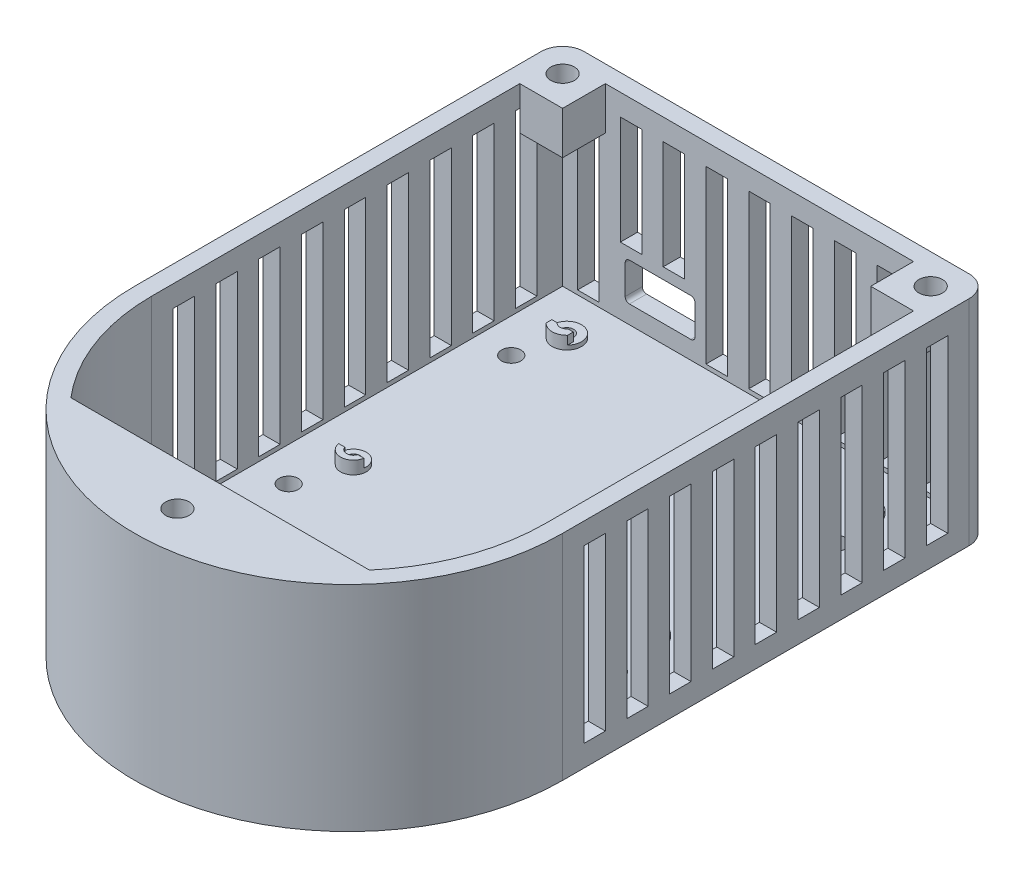
SolidWorks part; units mm, degrees
ref_plane "前视基准面" through (0, 0, 0) normal (0, 0, 1) x (1, 0, 0)
ref_plane "上视基准面" through (0, 0, 0) normal (0, 1, 0) x (1, 0, 0)
ref_plane "右视基准面" through (0, 0, 0) normal (1, 0, 0) x (0, 0, -1)
sketch "草图1" plane through (0, 0, 0) normal (0, 1, 0) x (1, 0, 0)
  line L2 (-50, -50) -> (-50, 50)
  line L3 (-50, 50) -> (50, 50)
  line L4 (50, -50) -> (50, 50)
  line L5 (-50, -50) -> (50, 50) construction
  line L6 (-50, 50) -> (50, -50) construction
  arc A1 (-50, -50) -> (50, -50) centre (0, -50) ccw
  point P0 (0, 0)
  dimension "D3" = 50
  dimension "D1" = 100
  dimension "D2" = 100
extrude "凸台-拉伸1" add sketch "草图1" along normal blind 50
shell "抽壳1" thickness 4
sketch "草图2" plane through (0, 4, 0) normal (0, 1, 0) x (1, 0, 0)
  line L0 (0, 0) -> (0, 50000) construction
  circle A7 centre (35.6323, -14.6895) radius 3
  circle A9 centre (35.7606, 35.3104) radius 3
  circle A10 centre (-35, 36) radius 3.4255
  circle A11 centre (-34.3676, -14.5099) radius 3
  dimension "D3" = 6
  dimension "D4" = 6
  dimension "D1" = 6
  dimension "D2" = 6.851
extrude "凸台-拉伸2" add sketch "草图2" along normal blind 3
sketch "草图4" plane through (0, 7, 0) normal (0, 1, 0) x (1, 0, 0)
  circle A0 centre (-34.3676, -14.5099) radius 1.6
  circle A1 centre (-35, 36) radius 1.6
  circle A2 centre (35.7606, 35.3104) radius 1.6
  circle A3 centre (35.6323, -14.6895) radius 1.6
extrude "切除-拉伸2" cut sketch "草图4" against normal blind 4
sketch "草图7" plane through (0, 4, 0) normal (0, 1, 0) x (1, 0, 0)
  line L0 (0, 0) -> (-50000, 0) construction
  line L1 (0, 0) -> (0, 50000) construction
  line L2 (46, 46) -> (-46, 46) construction
  line L4 (-46, 46) -> (-46, -50) construction
  circle A0 centre (-38, 26) radius 2.25
  circle A1 centre (38, 26) radius 2.25
  circle A2 centre (38, -26) radius 2.25
  circle A3 centre (-38, -26) radius 2.25
  dimension "D1" = 20
  dimension "D2" = 4.5
  dimension "D3" = 8
extrude "切除-拉伸4" cut sketch "草图7" against normal blind 5
sketch "草图8" plane through (50, 0, 0) normal (1, 0, 0) x (0, 0, -1)
  line L0 (-50, 50) -> (-50, 0) construction
  line L1 (-45, 45) -> (-40, 45)
  line L2 (-45, 45) -> (-45, 5)
  line L3 (-45, 5) -> (-40, 5)
  line L4 (-40, 45) -> (-40, 5)
  line L5 (-50, 50) -> (50, 50) construction
  line L6 (-50, 0) -> (50, 0) construction
  line L7 (-35, 45) -> (-35, 5)
  line L8 (-35, 45) -> (-30, 45)
  line L9 (-30, 45) -> (-30, 5)
  line L10 (-35, 5) -> (-30, 5)
  line L11 (-25, 45) -> (-25, 5)
  line L12 (-25, 45) -> (-20, 45)
  line L13 (-20, 45) -> (-20, 5)
  line L14 (-25, 5) -> (-20, 5)
  line L15 (-15, 45) -> (-15, 5)
  line L16 (-15, 45) -> (-10, 45)
  line L17 (-10, 45) -> (-10, 5)
  line L18 (-15, 5) -> (-10, 5)
  line L19 (-5, 45) -> (-5, 5)
  line L20 (-5, 45) -> (0, 45)
  line L21 (0, 45) -> (0, 5)
  line L22 (-5, 5) -> (0, 5)
  line L23 (5, 45) -> (5, 5)
  line L24 (5, 45) -> (10, 45)
  line L25 (10, 45) -> (10, 5)
  line L26 (5, 5) -> (10, 5)
  line L27 (15, 45) -> (15, 5)
  line L28 (15, 45) -> (20, 45)
  line L29 (20, 45) -> (20, 5)
  line L30 (15, 5) -> (20, 5)
  line L31 (25, 45) -> (25, 5)
  line L32 (25, 45) -> (30, 45)
  line L33 (30, 45) -> (30, 5)
  line L34 (25, 5) -> (30, 5)
  line L35 (35, 45) -> (35, 5)
  line L36 (35, 45) -> (40, 45)
  line L37 (40, 45) -> (40, 5)
  line L38 (35, 5) -> (40, 5)
  dimension "D1" = 5
  dimension "D2" = 5
  dimension "D3" = 5
  dimension "D4" = 5
  dimension "D5" = 9
extrude "切除-拉伸5" cut sketch "草图8" against normal blind 144
sketch "草图9" plane through (0, 0, -50) normal (0, 0, -1) x (-1, 0, 0)
  line L0 (-50, 0) -> (50, 0) construction
  line L1 (-2.5, 45) -> (2.5, 45)
  line L2 (-2.5, 45) -> (-2.5, 5)
  line L3 (-2.5, 5) -> (2.5, 5)
  line L4 (2.5, 45) -> (2.5, 5)
  line L5 (-50, 50) -> (50, 50) construction
  line L6 (7.5, 45) -> (7.5, 5)
  line L7 (7.5, 45) -> (12.5, 45)
  line L8 (12.5, 45) -> (12.5, 5)
  line L9 (7.5, 5) -> (12.5, 5)
  line L10 (17.5, 45) -> (17.5, 5)
  line L11 (17.5, 45) -> (22.5, 45)
  line L12 (22.5, 45) -> (22.5, 5)
  line L13 (17.5, 5) -> (22.5, 5)
  line L14 (27.5, 45) -> (27.5, 5)
  line L15 (27.5, 45) -> (32.5, 45)
  line L16 (32.5, 45) -> (32.5, 5)
  line L17 (27.5, 5) -> (32.5, 5)
  line L18 (37.5, 45) -> (37.5, 5)
  line L19 (37.5, 45) -> (42.5, 45)
  line L20 (42.5, 45) -> (42.5, 5)
  line L21 (37.5, 5) -> (42.5, 5)
  line L22 (-12.5, 45) -> (-12.5, 5)
  line L23 (-12.5, 45) -> (-7.5, 45)
  line L24 (-7.5, 45) -> (-7.5, 5)
  line L25 (-12.5, 5) -> (-7.5, 5)
  line L26 (-22.5, 45) -> (-22.5, 5)
  line L27 (-22.5, 45) -> (-17.5, 45)
  line L28 (-17.5, 45) -> (-17.5, 5)
  line L29 (-22.5, 5) -> (-17.5, 5)
  line L30 (-32.5, 45) -> (-32.5, 5)
  line L31 (-32.5, 45) -> (-27.5, 45)
  line L32 (-27.5, 45) -> (-27.5, 5)
  line L33 (-32.5, 5) -> (-27.5, 5)
  line L34 (-42.5, 45) -> (-42.5, 5)
  line L35 (-42.5, 45) -> (-37.5, 45)
  line L36 (-37.5, 45) -> (-37.5, 5)
  line L37 (-42.5, 5) -> (-37.5, 5)
  point P8 (0, 5)
  dimension "D1" = 5
  dimension "D2" = 5
  dimension "D3" = 5
  dimension "D4" = 5
  dimension "D5" = 5
extrude "切除-拉伸6" cut sketch "草图9" against normal blind 28
sketch "草图5" plane through (0, 50, 0) normal (0, 1, 0) x (1, 0, 0)
  line L0 (-34.8712, -80) -> (34.8712, -80)
  line L2 (-46, 46) -> (-36, 46)
  line L3 (-46, 46) -> (-46, 36)
  line L4 (-46, 36) -> (-36, 36)
  line L5 (-36, 46) -> (-36, 36)
  line L6 (46, 46) -> (36, 46)
  line L7 (46, 46) -> (46, 36)
  line L8 (46, 36) -> (36, 36)
  line L9 (36, 46) -> (36, 36)
  arc A0 (-46, -50) -> (46, -50) centre (0, -50) ccw construction
  arc A1 (-34.8712, -80) -> (34.8712, -80) centre (0, -50) ccw
  line M6 (46, 46) -> (46, -50)
  arc M7 (46, -50) -> (-46, -50) centre (0, -50) cw
  line M8 (-46, -50) -> (-46, 46)
  line M9 (-46, 46) -> (46, 46)
  dimension "D1" = 10
  dimension "D2" = 10
  dimension "D3" = 10
  dimension "D4" = 10
  dimension "D5" = 30
extrude "凸台-拉伸4" add sketch "草图5" against normal blind 10 contours L5 L4 M9 M8 | L9 L8 M9 M6 | L0 M7
sketch "草图6" plane through (0, 50, 0) normal (0, 1, 0) x (1, 0, 0)
  line L0 (0, 0) -> (0, 50000) construction
  line L1 (50, 50) -> (-50, 50) construction
  line L2 (-50, 50) -> (-50, -50) construction
  circle A0 centre (43, 43) radius 2.75
  circle A1 centre (0, -90) radius 2.75
  circle A2 centre (-43, 43) radius 2.75
  circle A3 centre (0, -50) radius 4.4958 construction
  dimension "D1" = 5.5
  dimension "D2" = 5.5
  dimension "D3" = 5.5
  dimension "D4" = 40
  dimension "D5" = 7
  dimension "D6" = 7
extrude "切除-拉伸3" cut sketch "草图6" against normal blind 4
fillet "圆角1" radius 5 2 edges at (-50, 25, -50) (50, 25, -50)
sketch "草图13" plane through (0, 0, -50) normal (0, 0, -1) x (-1, 0, 0)
  line L0 (23.2054, 8.2293) -> (23.2054, -49983.3) construction
  line L1 (23.2054, 1017.4869) -> (23.2054, 17.0934) construction
  line L2 (16.2554, 16.7) -> (30.1554, 16.7) construction
  line L3 (15.0335, 17.0934) -> (15.0335, 8.2293)
  line L4 (15.0335, 17.0934) -> (31.3774, 17.0934)
  line L6 (15.0335, 8.2293) -> (31.3774, 8.2293)
  line L7 (31.3774, 17.0934) -> (31.3774, 8.2293)
  line L9 (14.4187, 19.6784) -> (34.5969, 19.6784)
  line L10 (14.4187, 19.6784) -> (14.4187, 3.9395)
  line L11 (14.4187, 3.9395) -> (34.5969, 3.9395)
  line L12 (34.5969, 19.6784) -> (34.5969, 3.9395)
  point P6 (23.2054, 16.7)
extrude "凸台-拉伸6" add sketch "草图13" against normal blind 4
sketch "草图14" plane through (0, 0, -50) normal (0, 0, -1) x (-1, 0, 0)
  line L1 (15.0335, 17.0934) -> (31.3774, 17.0934)
  line L2 (15.0335, 17.0934) -> (15.0335, 8.2293)
  line L3 (15.0335, 8.2293) -> (31.3774, 8.2293)
  line L4 (31.3774, 17.0934) -> (31.3774, 8.2293)
extrude "切除-拉伸8" cut sketch "草图14" against normal blind 10
fillet "圆角2" radius 1 4 edges at (-15.0335, 8.2293, -48) (-31.3774, 8.2293, -48) (-31.3774, 17.0934, -48) (-15.0335, 17.0934, -48)
